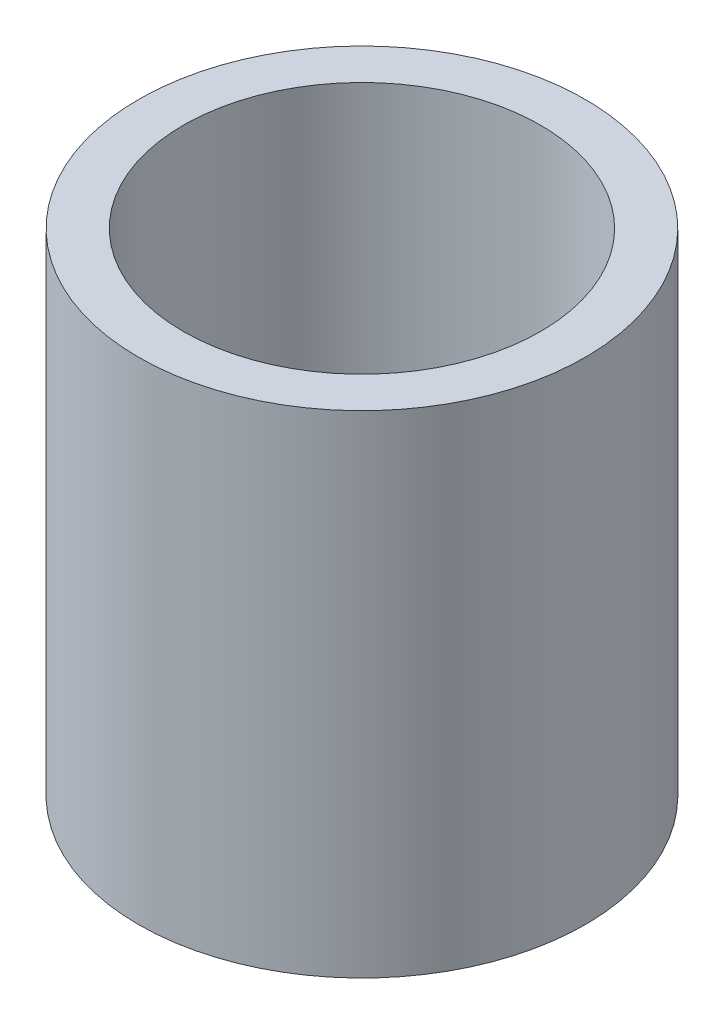
SolidWorks part; units mm, degrees
ref_plane "Front Plane" through (0, 0, 0) normal (0, 0, 1) x (1, 0, 0)
ref_plane "Top Plane" through (0, 0, 0) normal (0, 1, 0) x (1, 0, 0)
ref_plane "Right Plane" through (0, 0, 0) normal (1, 0, 0) x (0, 0, -1)
sketch "Sketch1" plane through (0, 0, 0) normal (0, 1, 0) x (1, 0, 0)
  circle A0 centre (0, 0) radius 15.875
  circle A1 centre (0, 0) radius 12.7
  dimension "D1" = 31.75
  dimension "D2" = 25.4
extrude "Boss-Extrude1" add sketch "Sketch1" along normal blind 34.925
